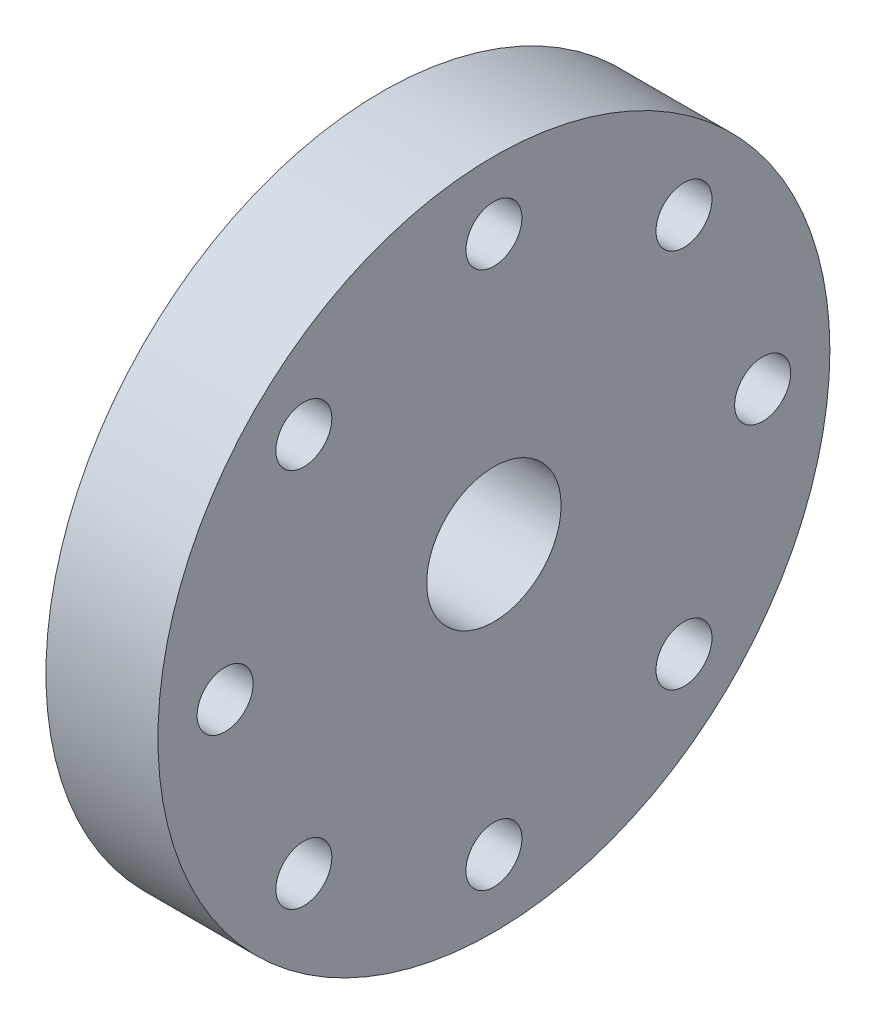
SolidWorks part; units mm, degrees
ref_plane "正面" through (0, 0, 0) normal (0, 0, 1) x (1, 0, 0)
ref_plane "平面" through (0, 0, 0) normal (0, 1, 0) x (1, 0, 0)
ref_plane "右側面" through (0, 0, 0) normal (1, 0, 0) x (0, 0, -1)
sketch "ｽｹｯﾁ1" plane through (0, 0, 0) normal (1, 0, 0) x (0, 0, -1)
  circle A0 centre (27.2138, 17.7095) radius 15
  circle A1 centre (27.2138, 29.7095) radius 1.25
  circle A2 centre (35.6991, 26.1947) radius 1.25
  circle A3 centre (18.7285, 26.1947) radius 1.25
  circle A4 centre (15.2138, 17.7095) radius 1.25
  circle A6 centre (35.6991, 9.2242) radius 1.25
  circle A7 centre (39.2138, 17.7095) radius 1.25
  circle A8 centre (18.7285, 9.2242) radius 1.25
  circle A9 centre (27.2138, 5.7095) radius 1.25
extrude "ﾎﾞｽ - 押し出し2" add sketch "ｽｹｯﾁ1" along normal blind 5
ref_plane "平面1" through (0, 0, 0) normal (-1, 0, 0) x (0, 0, 1)
sketch "ｽｹｯﾁ3" plane through (0, 0, 0) normal (1, 0, 0) x (0, 0, -1)
  circle A0 centre (27.2138, 17.7095) radius 5
extrude "ﾎﾞｽ - 押し出し4" add sketch "ｽｹｯﾁ3" against normal blind 1
ref_plane "平面2" through (5, 0, 0) normal (1, 0, 0) x (0, 0, -1)
sketch "ｽｹｯﾁ4" plane through (5, 0, 0) normal (1, 0, 0) x (0, 0, -1)
  circle A0 centre (27.2138, 17.7095) radius 3
extrude "ｶｯﾄ - 押し出し1" cut sketch "ｽｹｯﾁ4" against normal blind 5.5
sketch "ｽｹｯﾁ5" plane through (0, 0, 0) normal (-1, 0, 0) x (0, 0, 1)
  circle A0 centre (-27.2138, 17.7095) radius 1.5
extrude "ｶｯﾄ - 押し出し2" cut sketch "ｽｹｯﾁ5" against normal blind 5.5 and the other way blind 78
